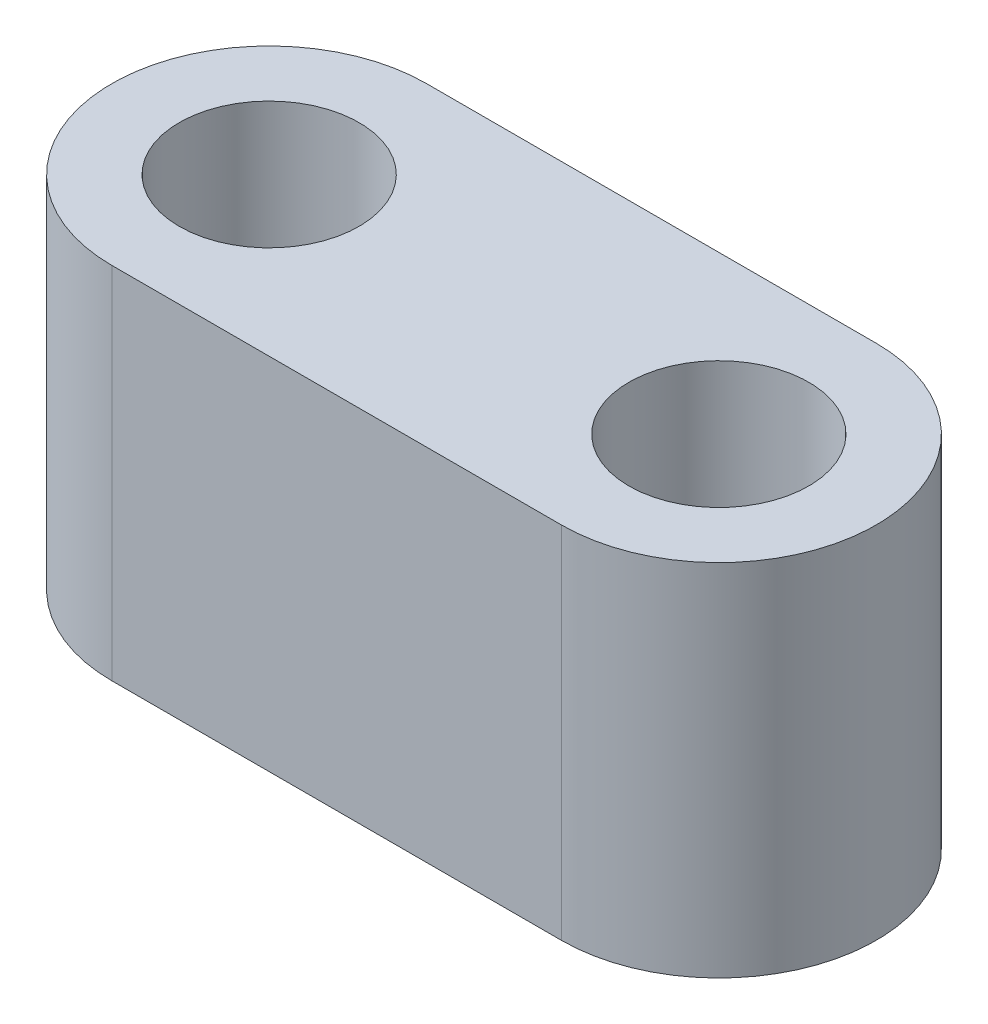
SolidWorks part; units mm, degrees
material "AISI 304"
ref_plane "Front Plane" through (0, 0, 0) normal (0, 0, 1) x (1, 0, 0)
ref_plane "Top Plane" through (0, 0, 0) normal (0, 1, 0) x (1, 0, 0)
ref_plane "Right Plane" through (0, 0, 0) normal (1, 0, 0) x (0, 0, -1)
sketch "Sketch1" plane through (0, 0, 0) normal (0, 1, 0) x (1, 0, 0)
  line L0 (-2.5, 0) -> (2.5, 0) construction
  line L1 (-2.5, 1.75) -> (2.5, 1.75)
  line L2 (-2.5, -1.75) -> (2.5, -1.75)
  arc A0 (-2.5, 1.75) -> (-2.5, -1.75) centre (-2.5, 0) ccw
  arc A1 (2.5, -1.75) -> (2.5, 1.75) centre (2.5, 0) ccw
  circle A2 centre (2.5, 0) radius 1
  circle A3 centre (-2.5, 0) radius 1
  point P2 (0, 0)
  dimension "D1" = 2
  dimension "D2" = 3.5
  dimension "D3" = 5
extrude "Boss-Extrude1" add sketch "Sketch1" along normal blind 4
